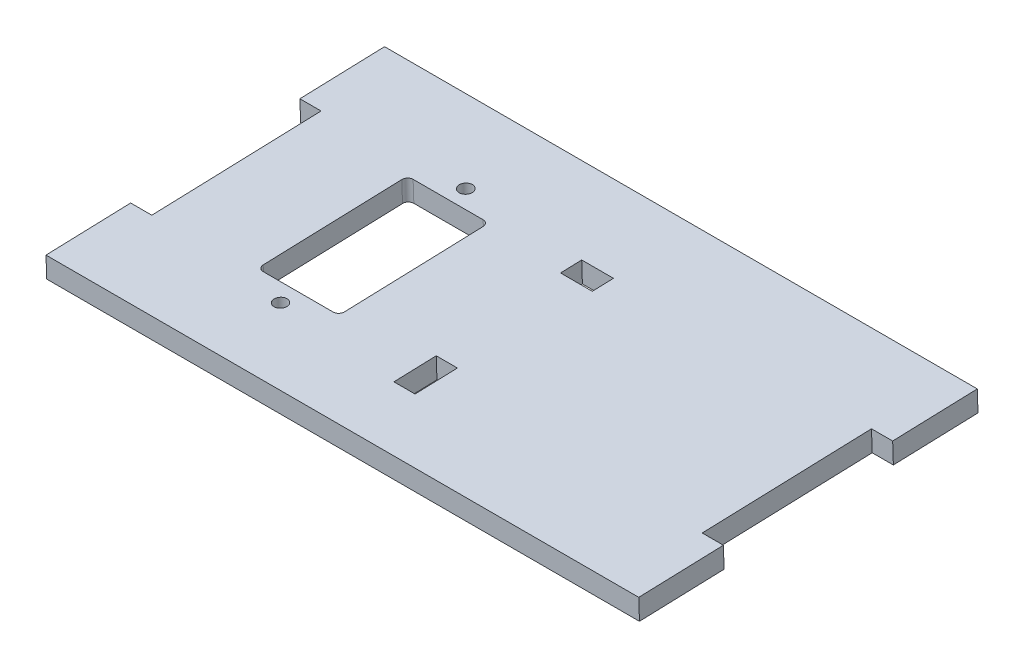
SolidWorks part; units mm, degrees
material "Balsa"
ref_plane "Front Plane" through (0, 0, 0) normal (0, 0, 1) x (1, 0, 0)
ref_plane "Top Plane" through (0, 0, 0) normal (0, 1, 0) x (1, 0, 0)
ref_plane "Right Plane" through (0, 0, 0) normal (1, 0, 0) x (0, 0, -1)
ref_plane "Plane1" through (0, 88.9799, 2.9515) normal (0, 0.9995, 0.0332) x (1, 0, 0)
sketch "Sketch3" plane through (0, 88.9799, 2.9515) normal (0, 0.9995, 0.0332) x (1, 0, 0)
  line L0 (13.6208, -483.7344) -> (3.1208, -483.7344) construction
  line L1 (2.2708, -484.5844) -> (2.2708, -505.3844) construction
  line L2 (3.1208, -506.2344) -> (13.6208, -506.2344) construction
  line L3 (14.4708, -505.3844) -> (14.4708, -484.5844) construction
  line L4 (26.3031, -481.6339) -> (26.3031, -484.8089)
  line L5 (31.0656, -481.6339) -> (26.3031, -481.6339)
  line L6 (31.0656, -484.8089) -> (31.0656, -481.6339)
  line L7 (26.3031, -484.8089) -> (31.0656, -484.8089)
  line L8 (26.3031, -481.6339) -> (26.3031, -484.8089)
  line L9 (31.0656, -481.6339) -> (26.3031, -481.6339)
  line L10 (31.0656, -484.8089) -> (31.0656, -481.6339)
  line L11 (26.3031, -484.8089) -> (31.0656, -484.8089)
  line L12 (73.1309, -481.8244) -> (73.1309, -469.1244)
  line L13 (73.1309, -469.1244) -> (-15.7691, -469.1244)
  line L14 (-15.7691, -469.1244) -> (-15.7691, -481.8244)
  line L15 (-15.7691, -481.8244) -> (-12.5941, -481.8244)
  line L16 (-12.5941, -481.8244) -> (-12.5941, -507.2244)
  line L17 (-12.5941, -507.2244) -> (-15.7691, -507.2244)
  line L18 (-15.7691, -507.2244) -> (-15.7691, -519.9244)
  line L19 (-15.7691, -519.9244) -> (73.1309, -519.9244)
  line L20 (73.1309, -519.9244) -> (73.1309, -507.2244)
  line L21 (73.1309, -507.2244) -> (69.9559, -507.2244)
  line L22 (69.9559, -507.2244) -> (69.9559, -481.8244)
  line L23 (69.9559, -481.8244) -> (73.1309, -481.8244)
  line L24 (73.1309, -481.8244) -> (73.1309, -469.1244)
  line L25 (73.1309, -469.1244) -> (-15.7691, -469.1244)
  line L26 (-15.7691, -469.1244) -> (-15.7691, -481.8244)
  line L27 (-15.7691, -481.8244) -> (-12.5941, -481.8244)
  line L28 (-12.5941, -481.8244) -> (-12.5941, -507.2244)
  line L29 (-12.5941, -507.2244) -> (-15.7691, -507.2244)
  line L30 (-15.7691, -507.2244) -> (-15.7691, -519.9244)
  line L31 (-15.7691, -519.9244) -> (73.1309, -519.9244)
  line L32 (73.1309, -519.9244) -> (73.1309, -507.2244)
  line L33 (73.1309, -507.2244) -> (69.9559, -507.2244)
  line L34 (69.9559, -507.2244) -> (69.9559, -481.8244)
  line L35 (69.9559, -481.8244) -> (73.1309, -481.8244)
  line L36 (30.2684, -510.6013) -> (30.2684, -504.2513)
  line L37 (27.0934, -510.6013) -> (30.2684, -510.6013)
  line L38 (27.0934, -504.2513) -> (27.0934, -510.6013)
  line L39 (30.2684, -504.2513) -> (27.0934, -504.2513)
  line L40 (30.2684, -510.6013) -> (30.2684, -504.2513)
  line L41 (27.0934, -510.6013) -> (30.2684, -510.6013)
  line L42 (27.0934, -504.2513) -> (27.0934, -510.6013)
  line L43 (30.2684, -504.2513) -> (27.0934, -504.2513)
  line L44 (13.6208, -483.7344) -> (3.1208, -483.7344)
  line L45 (2.2708, -484.5844) -> (2.2708, -505.3844)
  line L46 (3.1208, -506.2344) -> (13.6208, -506.2344)
  line L47 (14.4708, -505.3844) -> (14.4708, -484.5844)
  arc A0 (9.3503, -508.8844) -> (8.3708, -507.9049) centre (8.3708, -508.8844) ccw construction
  arc A1 (8.3708, -507.9049) -> (7.3912, -508.8844) centre (8.3708, -508.8844) ccw construction
  arc A2 (8.3708, -509.8639) -> (9.3503, -508.8844) centre (8.3708, -508.8844) ccw construction
  arc A3 (7.3912, -508.8844) -> (8.3708, -509.8639) centre (8.3708, -508.8844) ccw construction
  arc A4 (8.3708, -482.0844) -> (9.3708, -481.0844) centre (8.3708, -481.0844) ccw construction
  arc A5 (7.3708, -481.0844) -> (8.3708, -482.0844) centre (8.3708, -481.0844) ccw construction
  arc A6 (9.3708, -481.0844) -> (8.3708, -480.0844) centre (8.3708, -481.0844) ccw construction
  arc A7 (8.3708, -480.0844) -> (7.3708, -481.0844) centre (8.3708, -481.0844) ccw construction
  arc A8 (14.4708, -484.5844) -> (13.6208, -483.7344) centre (13.6208, -484.5844) ccw construction
  arc A9 (3.1208, -483.7344) -> (2.2708, -484.5844) centre (3.1208, -484.5844) ccw construction
  arc A10 (2.2708, -505.3844) -> (3.1208, -506.2344) centre (3.1208, -505.3844) ccw construction
  arc A11 (13.6208, -506.2344) -> (14.4708, -505.3844) centre (13.6208, -505.3844) ccw construction
  arc A12 (9.3503, -508.8844) -> (8.3708, -507.9049) centre (8.3708, -508.8844) ccw
  arc A13 (8.3708, -507.9049) -> (7.3912, -508.8844) centre (8.3708, -508.8844) ccw
  arc A14 (8.3708, -509.8639) -> (9.3503, -508.8844) centre (8.3708, -508.8844) ccw
  arc A15 (7.3912, -508.8844) -> (8.3708, -509.8639) centre (8.3708, -508.8844) ccw
  arc A16 (8.3708, -482.0844) -> (9.3708, -481.0844) centre (8.3708, -481.0844) ccw
  arc A17 (7.3708, -481.0844) -> (8.3708, -482.0844) centre (8.3708, -481.0844) ccw
  arc A18 (9.3708, -481.0844) -> (8.3708, -480.0844) centre (8.3708, -481.0844) ccw
  arc A19 (8.3708, -480.0844) -> (7.3708, -481.0844) centre (8.3708, -481.0844) ccw
  arc A20 (14.4708, -484.5844) -> (13.6208, -483.7344) centre (13.6208, -484.5844) ccw
  arc A21 (3.1208, -483.7344) -> (2.2708, -484.5844) centre (3.1208, -484.5844) ccw
  arc A22 (2.2708, -505.3844) -> (3.1208, -506.2344) centre (3.1208, -505.3844) ccw
  arc A23 (13.6208, -506.2344) -> (14.4708, -505.3844) centre (13.6208, -505.3844) ccw
  dimension "D1" = 0
  dimension "D2" = 0
  dimension "D3" = 0
extrude "Boss-Extrude2" add sketch "Sketch3" along normal blind 3.175
